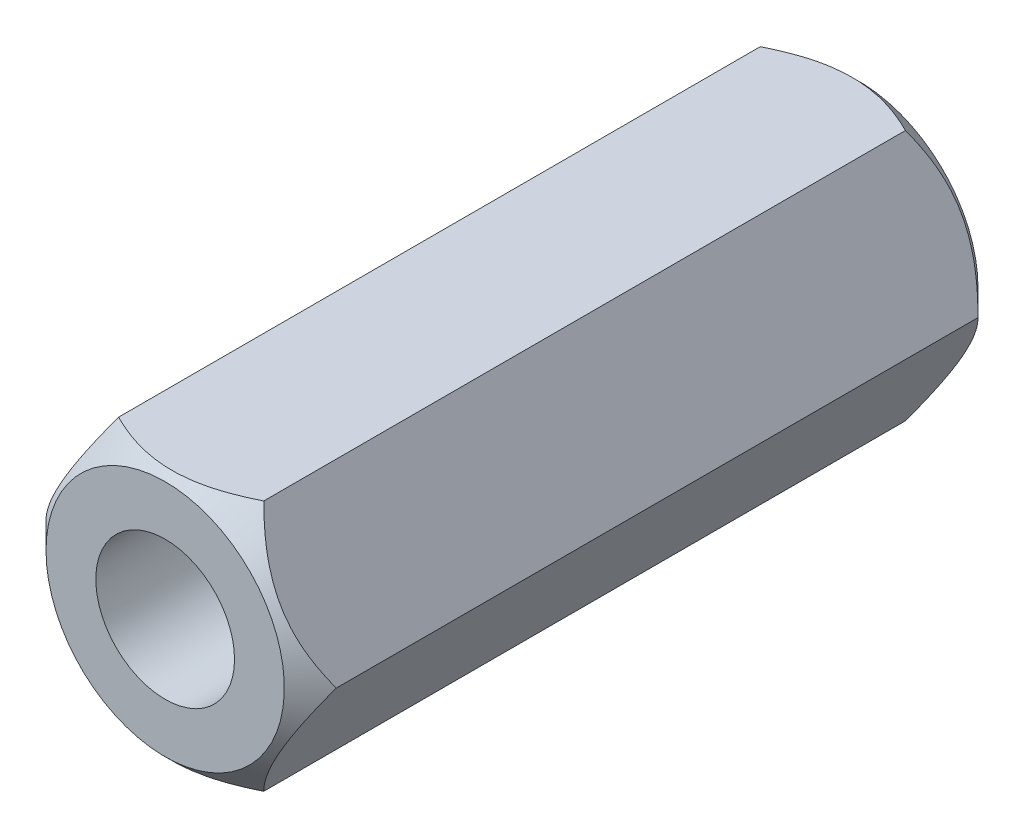
SolidWorks part; units mm, degrees
ref_plane "Спереди" through (0, 0, 0) normal (0, 0, 1) x (1, 0, 0)
ref_plane "Сверху" through (0, 0, 0) normal (0, 1, 0) x (1, 0, 0)
ref_plane "Справа" through (0, 0, 0) normal (1, 0, 0) x (0, 0, -1)
sketch "Эскиз1" plane through (0, 0, 0) normal (0, 0, 1) x (1, 0, 0)
  line L1 (1.6743, 0) -> (0.8372, 1.45)
  line L2 (0.8372, 1.45) -> (-0.8372, 1.45)
  line L3 (-0.8372, 1.45) -> (-1.6743, 0)
  line L4 (-1.6743, 0) -> (-0.8372, -1.45)
  line L5 (-0.8372, -1.45) -> (0.8372, -1.45)
  line L6 (0.8372, -1.45) -> (1.6743, 0)
  circle A0 centre (0, 0) radius 1.45 construction
  dimension "D1" = 2.9
extrude "Бобышка-Вытянуть1" add sketch "Эскиз1" along normal mid plane 8
hole_wizard "Отверстие обработанное метчиком M21" positions "Эскиз2" profile "Эскиз3" tap size "M2" standard "DIN" end condition through all
sketch "Эскиз2" plane through (0, 0, 4) normal (0, 0, 1) x (1, 0, 0)
  point P0 (0, 0)
sketch "Эскиз3" plane through (0, 0, 4) normal (1, 0, 0) x (0, -1, 0)
  line L0 (0, 0) -> (0, 8)
  line L1 (0, 8) -> (0.8, 8)
  line L2 (0.8, 8) -> (0.8, 0)
  line L5 (0.8, 0) -> (0, 0)
  line L11 (0, -6.35) -> (0, 107.95) construction
  dimension "Диаметр проходного сверла" = 1.6
  dimension "Глубина проходного сверла" = 8
cosmetic thread "Отверстие резьбы1" parameters "D2"=2
ref_axis "Ось1" through (0, 0, -4) along (0, 0, 1)
sketch "Эскиз4" plane through (0, 0, 0) normal (0, 1, 0) x (0, 0, -1)
  line L0 (4, 1.3743) -> (3.7, 1.6743)
  line L1 (4, -1.6743) -> (4, -0.8372) construction
  line L3 (3.7, 1.6743) -> (4, 1.6743)
  line L4 (4, 1.6743) -> (4, 1.3743)
  line L5 (0, 55) -> (0, -55) construction
  line L6 (-4, 1.6743) -> (-4, 1.3743)
  line L7 (-3.7, 1.6743) -> (-4, 1.6743)
  line L8 (-4, 1.3743) -> (-3.7, 1.6743)
  dimension "D1" = 0.3
revolve "Вырез-Повернуть1" cut sketch "Эскиз4" angle 360 about axis through (0, 0, -4) along (0, 0, 1)
